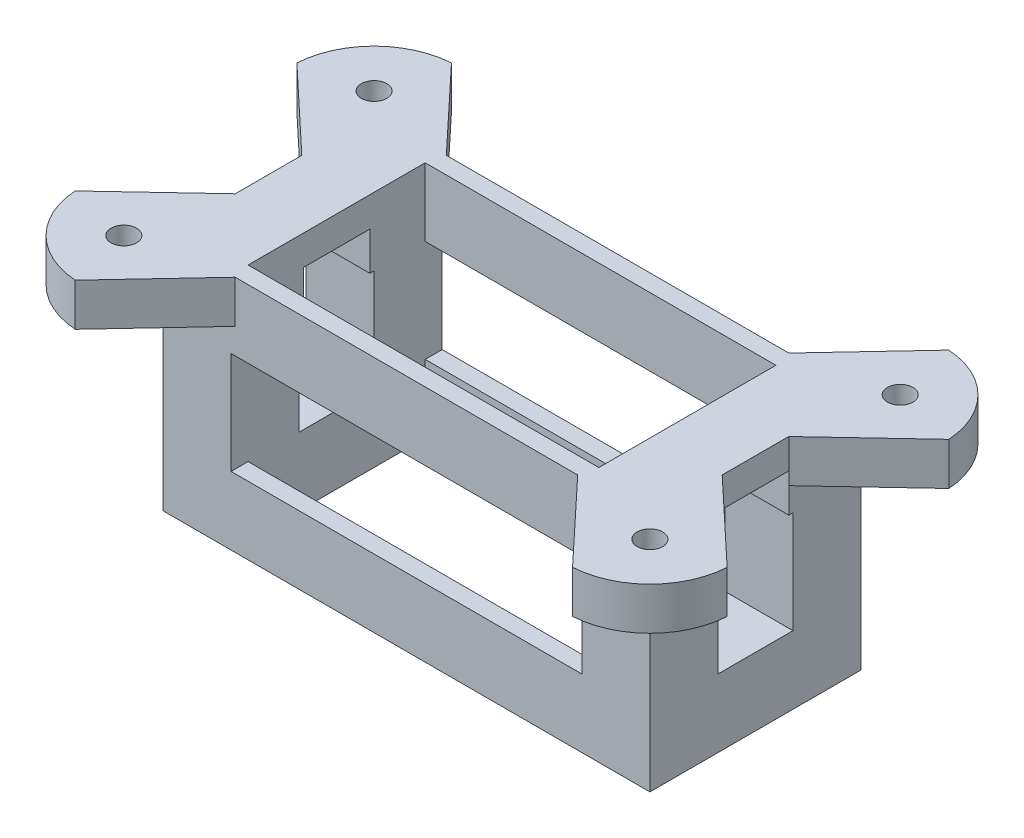
SolidWorks part; units mm, degrees
ref_plane "Front Plane" through (0, 0, 0) normal (0, 0, 1) x (1, 0, 0)
ref_plane "Top Plane" through (0, 0, 0) normal (0, 1, 0) x (1, 0, 0)
ref_plane "Right Plane" through (0, 0, 0) normal (1, 0, 0) x (0, 0, -1)
sketch "Sketch2" plane through (0, 0, 0) normal (0, -1, 0) x (1, 0, 0)
  line L0 (20.2, 0) -> (-20.2, 0) construction
  line L1 (20.2, -20) -> (20.2, 0) construction
  line L2 (-20.2, -20) -> (20.2, -20) construction
  line L3 (-20.2, 0) -> (-20.2, -20) construction
  line L4 (20.2, 0) -> (-20.2, 0)
  line L5 (20.2, -20) -> (20.2, 0)
  line L6 (-20.2, -20) -> (20.2, -20)
  line L7 (-20.2, 0) -> (-20.2, -20)
  line L8 (-20.6, -20.4) -> (20.6, -20.4)
  line L9 (20.6, -20.4) -> (20.6, 0.4)
  line L10 (20.6, 0.4) -> (-20.6, 0.4)
  line L11 (-20.6, 0.4) -> (-20.6, -20.4)
  line L12 (-28.6, -28.4) -> (28.6, -28.4)
  line L13 (28.6, -28.4) -> (28.6, 8.4)
  line L14 (28.6, 8.4) -> (-28.6, 8.4)
  line L15 (-28.6, 8.4) -> (-28.6, -28.4)
  line L16 (-28.6, -22.4) -> (28.6, -22.4)
  line L17 (-28.6, 2.4) -> (28.6, 2.4)
  circle A0 centre (24.9292, -15.5) radius 2.2
  circle A1 centre (24.9292, -4.5) radius 2.2
  circle A2 centre (-24.9292, -4.5) radius 2.2
  circle A3 centre (-24.9292, -15.5) radius 2.2
  circle M10 centre (10.2, -10) radius 35
  dimension "D3" = 6
  dimension "D4" = 6
  dimension "D1" = 0.4
  dimension "D2" = 8
extrude "Boss-Extrude2" add sketch "Sketch2" along normal blind 28 contours A3 A2 L17 L15 L16 M10 | A3 L16 L13 L17 A2 A1 A0 L11 L10 L9 L8 M10 | A2 M10 | A2 M10 | A3 M10 | A3 M10 | A1 | A0
sketch "Sketch4" plane through (-28.6, 0, 0) normal (-1, 0, 0) x (0, 0, 1)
  line L0 (2.4, -28) -> (-22.4, -28) construction
  line L1 (-5.6, -20) -> (-14.4, -20)
  line L2 (-5.6, -20) -> (-5.6, -8)
  line L3 (-5.6, -8) -> (-14.4, -8)
  line L4 (-14.4, -20) -> (-14.4, -8)
  line L5 (-5.6, -20) -> (-14.4, -8) construction
  line L6 (-5.6, -8) -> (-14.4, -20) construction
  line L7 (-22.4, -28) -> (-22.4, 0) construction
  line L8 (2.4, -28) -> (2.4, 0) construction
  line L9 (2.4, 0) -> (-22.4, 0) construction
  point P0 (-10, -14)
  dimension "D1" = 8
  dimension "D2" = 8
  dimension "D3" = 8
  dimension "D4" = 8
extrude "Cut-Extrude1" cut sketch "Sketch4" against normal blind 73
sketch "Sketch5" plane through (0, 0, 2.4) normal (0, 0, 1) x (1, 0, 0)
  line L0 (-28.6, -28) -> (28.6, -28) construction
  line L1 (20.6, -20) -> (-20.6, -20)
  line L2 (20.6, -20) -> (20.6, -8)
  line L3 (20.6, -8) -> (-20.6, -8)
  line L4 (-20.6, -20) -> (-20.6, -8)
  line L5 (20.6, -20) -> (-20.6, -8) construction
  line L6 (20.6, -8) -> (-20.6, -20) construction
  line L7 (-28.6, -28) -> (-28.6, 0) construction
  line L8 (-28.6, 0) -> (28.6, 0) construction
  line L9 (28.6, -28) -> (28.6, 0) construction
  point P0 (0, -14)
  dimension "D1" = 8
  dimension "D2" = 8
  dimension "D3" = 8
  dimension "D4" = 8
extrude "Cut-Extrude2" cut sketch "Sketch5" against normal blind 28
sketch "Sketch6" plane through (0, -28, 0) normal (0, -1, 0) x (1, 0, 0)
  circle A0 centre (-24.9292, -15.5) radius 1.25
  circle A1 centre (-24.9292, -4.5) radius 1.25
  circle A2 centre (24.9292, -15.5) radius 1.25
  circle A3 centre (24.9292, -4.5) radius 1.25
  dimension "D1" = 2.5
  dimension "D2" = 2.5
extrude "Cut-Extrude3" cut sketch "Sketch6" against normal blind 7
sketch "Sketch7" plane through (0, 0, 0) normal (0, 1, 0) x (1, 0, 0)
  line L0 (-28.6, -2.4) -> (-30.9, -4.7) construction
  line L1 (-28.6, -2.4) -> (-28.6, 22.4) construction
  line L2 (-28.6, 0.6) -> (-33.9435, -4.4239)
  line L3 (-25.6, -2.4) -> (-30.6138, -7.7473)
  line L5 (-28.6, -2.4) -> (28.6, -2.4) construction
  line L6 (-31.3262, -5.1262) -> (-30.1033, -3.9033) construction
  line L7 (-28.6, -2.4) -> (28.6, -2.4) construction
  line L9 (-33.016, -6.816) -> (-31.1924, -4.9924) construction
  line L10 (28.6, 22.4) -> (28.6, -2.4) construction
  arc A0 (-33.9435, -4.4239) -> (-30.6138, -7.7473) centre (-28.6, -2.4) ccw
  circle A1 centre (-30.9, -4.7) radius 1.5
  line M6 (-28.6, 22.4) -> (-28.6, -2.4)
  line M7 (-28.6, -2.4) -> (28.6, -2.4)
  dimension "D1" = 3
  dimension "D5" = 5.7139
  dimension "D2" = 135
  dimension "D3" = 3
  dimension "D4" = 3
  dimension "D6" = 59.5
  dimension "D7" = 59.2138
  dimension "D8" = 62.5435
extrude "Boss-Extrude3" add sketch "Sketch7" against normal blind 5 contours L2 A0 L3 A1 M7 M6
ref_plane "Plane1" through (0, 0, 0) normal (-1, 0, 0) x (0, 0, 1)
mirror "Mirror1" about plane through (0, 0, 0) normal (-1, 0, 0) of "Boss-Extrude3"
ref_plane "Plane2" through (0, 0, -10) normal (0, 0, 1) x (1, 0, 0)
mirror "Mirror2" about plane through (0, 0, -10) normal (0, 0, 1) of "Mirror1", "Boss-Extrude3"
sketch "Sketch8" plane through (0, -5, 0) normal (0, -1, 0) x (1, 0, 0)
  line L4 (28.6, -22.4) -> (28.6, 2.4) construction
  line L5 (-28.6, 2.4) -> (28.6, 2.4) construction
  line L6 (28.6, -22.4) -> (28.6, 2.4)
  line L7 (-28.6, 2.4) -> (28.6, 2.4)
  line L8 (24.6, -9.851) -> (38.2939, 3.0237)
  line L9 (29.207, 12.0949) -> (16.3662, -1.6)
  line L10 (16.3662, -1.6) -> (24.6, -1.6)
  line L11 (24.6, -1.6) -> (24.6, -9.851)
  line L12 (28.6, -6.0903) -> (38.2939, 3.0237)
  line L13 (29.207, 12.0949) -> (20.1167, 2.4)
  circle A1 centre (30.9, 4.7) radius 1.5 construction
  arc A2 (38.2939, 3.0237) -> (29.207, 12.0949) centre (28.6, 2.4) ccw
  arc A3 (38.2939, 3.0237) -> (29.207, 12.0949) centre (28.6, 2.4) ccw
  circle A4 centre (30.9, 4.7) radius 1.5
  line M7 (28.6, -0.6) -> (33.9435, 4.4239)
  arc M8 (33.9435, 4.4239) -> (30.6138, 7.7473) centre (28.6, 2.4) ccw
  line M9 (30.6138, 7.7473) -> (25.6, 2.4)
  dimension "D1" = 4
extrude "Boss-Extrude4" add sketch "Sketch8" against normal up to surface (5 mm away) contours L12 A3 L13 L7 L6 M9 M8 M7 up to face at (0, 0, -10)
ref_plane "Plane3" through (0, 0, -10) normal (0, 0, -1) x (-1, 0, 0)
mirror "Mirror3" about plane through (0, 0, -10) normal (0, 0, -1) of "Boss-Extrude4"
mirror "Mirror4" about plane through (0, 0, 0) normal (-1, 0, 0) of "Mirror3", "Boss-Extrude4"
sketch "Sketch10" plane through (28.6, 0, 0) normal (1, 0, 0) x (0, 0, -1)
  line L0 (10, 0) -> (10, -3.5)
  line L2 (13.9097, 0) -> (6.0903, 0) construction
  line L3 (13.9097, -3.5) -> (6.0903, -3.5)
  line L4 (6.0903, 0) -> (6.0903, -5) construction
  line L5 (13.9097, -3.5) -> (13.9097, -8)
  line L6 (5.6, -8) -> (14.4, -8) construction
  line L7 (13.9097, -8) -> (6.0903, -8)
  line L8 (6.0903, -8) -> (6.0903, -3.5)
  point P6 (10, -3.5)
  line M4 (5.6, -8) -> (14.4, -8)
  line M8 (13.9097, -5) -> (13.9097, 0)
  line M10 (6.0903, 0) -> (6.0903, -5)
  dimension "D1" = 3.5
extrude "Cut-Extrude4" cut sketch "Sketch10" against normal through all contours L8 L5 L3 M4 M8 M10
